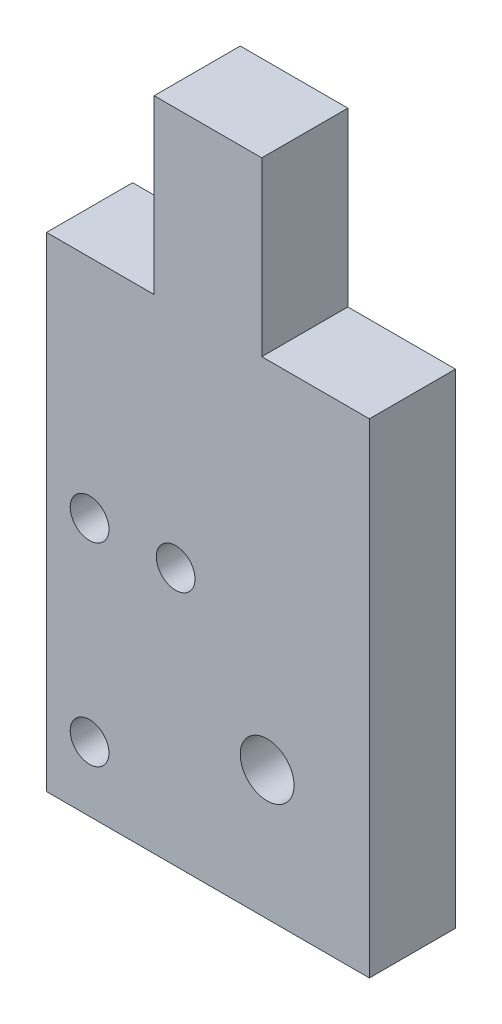
SolidWorks part; units mm, degrees
ref_plane "Front Plane" through (0, 0, 0) normal (0, 0, 1) x (1, 0, 0)
ref_plane "Top Plane" through (0, 0, 0) normal (0, 1, 0) x (1, 0, 0)
ref_plane "Right Plane" through (0, 0, 0) normal (1, 0, 0) x (0, 0, -1)
sketch "Sketch1" plane through (0, 0, 0) normal (0, 0, 1) x (1, 0, 0)
  line L0 (0, 57.15) -> (12.7, 57.15)
  line L1 (0, 0) -> (38.1, 0)
  line L5 (12.7, 57.15) -> (12.7, 77.47)
  line L6 (12.7, 77.47) -> (25.4, 77.47)
  line L7 (25.4, 77.47) -> (25.4, 57.15)
  line L8 (25.4, 57.15) -> (38.1, 57.15)
  line L9 (0, 57.15) -> (0, 0)
  line L10 (38.1, 57.15) -> (38.1, 0)
  line L11 (0, 74.3071) -> (10.16, 74.3071) construction
  line L12 (10.16, 74.3071) -> (10.16, 25.4) construction
  circle A0 centre (5.08, 7.62) radius 2.286
  circle A1 centre (5.08, 30.48) radius 2.286
  circle A2 centre (26.035, 15.24) radius 3.175
  circle A3 centre (15.24, 30.48) radius 2.286
  point P11 (29.21, 15.24)
  point P12 (22.86, 15.24)
  dimension "D3" = 7.62
  dimension "D5" = 4.572
  dimension "D6" = 4.572
  dimension "D8" = 29.21
  dimension "D9" = 12.7
  dimension "D10" = 20.32
  dimension "D13" = 5.08
  dimension "D14" = 4.572
  dimension "D1" = 38.1
  dimension "D2" = 5.08
  dimension "D4" = 22.86
  dimension "D7" = 22.86
  dimension "D11" = 10.16
  dimension "D12" = 25.4
  dimension "D15" = 5.08
extrude "Boss-Extrude1" add sketch "Sketch1" along normal blind 10.16
